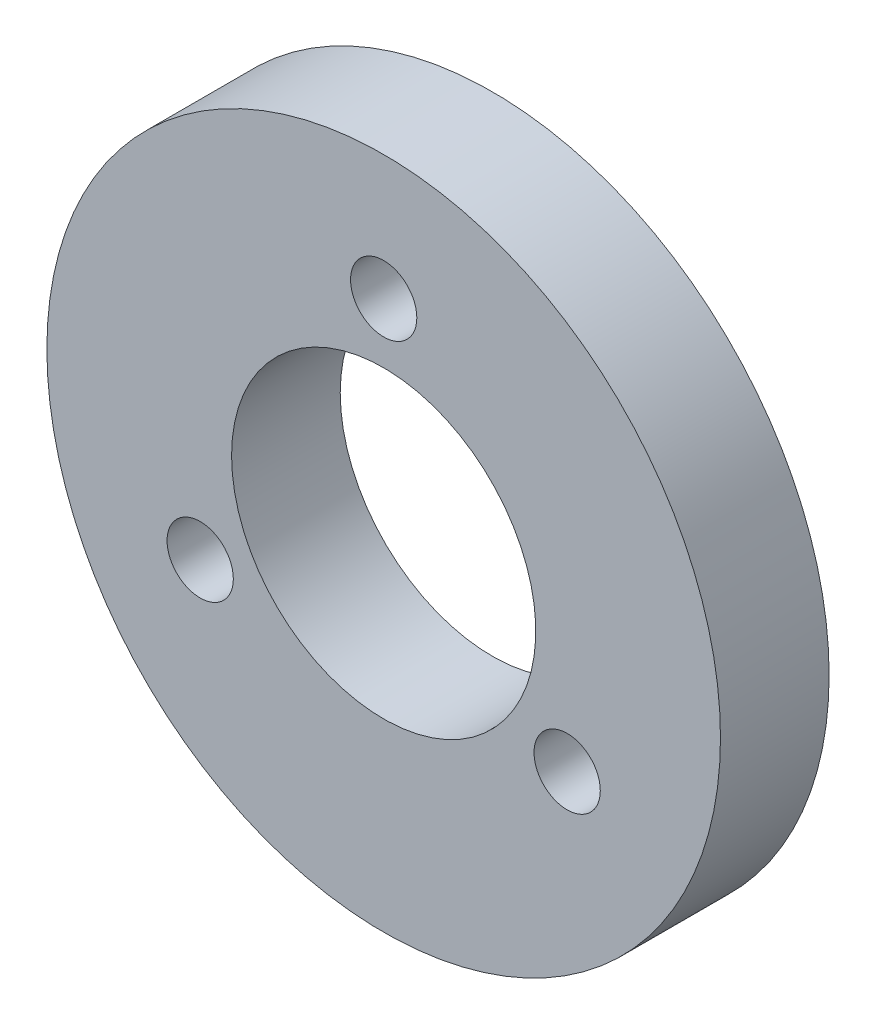
SolidWorks part; units mm, degrees
ref_plane "Front Plane" through (0, 0, 0) normal (0, 0, 1) x (1, 0, 0)
ref_plane "Top Plane" through (0, 0, 0) normal (0, 1, 0) x (1, 0, 0)
ref_plane "Right Plane" through (0, 0, 0) normal (1, 0, 0) x (0, 0, -1)
sketch "Sketch1" plane through (0, 0, 0) normal (0, 0, 1) x (1, 0, 0)
  circle A0 centre (0, 0) radius 15.5
  circle A1 centre (0, 0) radius 7
  dimension "D1" = 31
  dimension "D2" = 14
extrude "Boss-Extrude1" add sketch "Sketch1" along normal blind 5
sketch "Sketch2" plane through (0, 0, 5) normal (0, 0, 1) x (1, 0, 0)
  circle A1 centre (0, 9.75) radius 1.525
  circle A2 centre (8.4437, -4.875) radius 1.525
  circle A3 centre (-8.4437, -4.875) radius 1.525
  point P11 (0, 0)
  dimension "D2" = 3.05
  dimension "D3" = 3
extrude "Cut-Extrude1" cut sketch "Sketch2" against normal up to next
